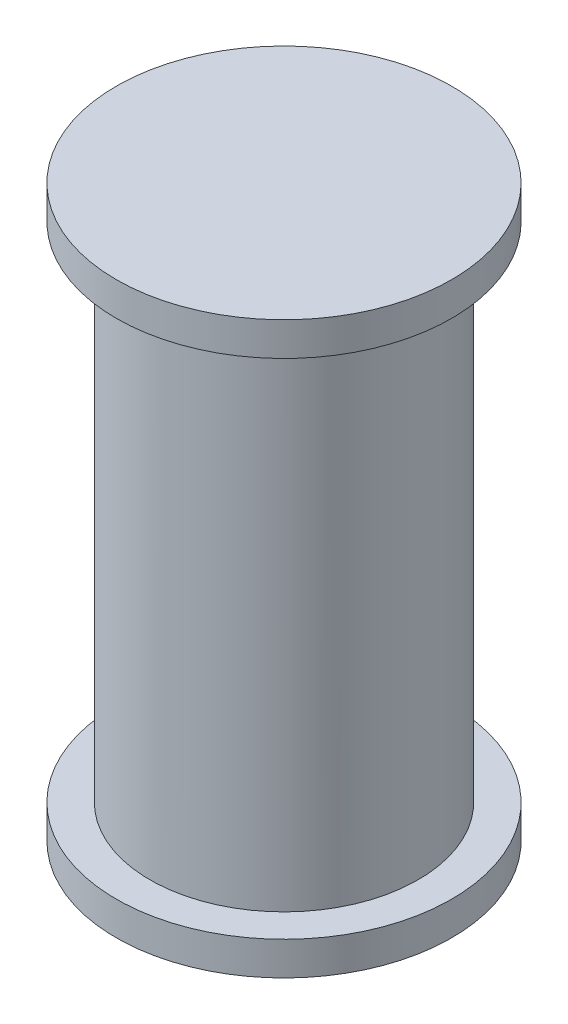
SolidWorks part; units mm, degrees
ref_plane "Alzado" through (0, 0, 0) normal (0, 0, 1) x (1, 0, 0)
ref_plane "Planta" through (0, 0, 0) normal (0, 1, 0) x (1, 0, 0)
ref_plane "Vista lateral" through (0, 0, 0) normal (1, 0, 0) x (0, 0, -1)
sketch "Croquis1" plane through (0, 0, 0) normal (0, 1, 0) x (1, 0, 0)
  circle A0 centre (0, 0) radius 4
extrude "Saliente-Extruir1" add sketch "Croquis1" along normal blind 15
sketch "Croquis2" plane through (0, 15, 0) normal (0, 1, 0) x (1, 0, 0)
  circle A0 centre (0, 0) radius 5
extrude "Saliente-Extruir2" add sketch "Croquis2" along normal blind 1
sketch "Croquis3" plane through (0, 0, 0) normal (0, -1, 0) x (1, 0, 0)
  circle A0 centre (0, 0) radius 5
extrude "Saliente-Extruir3" add sketch "Croquis3" along normal blind 1
